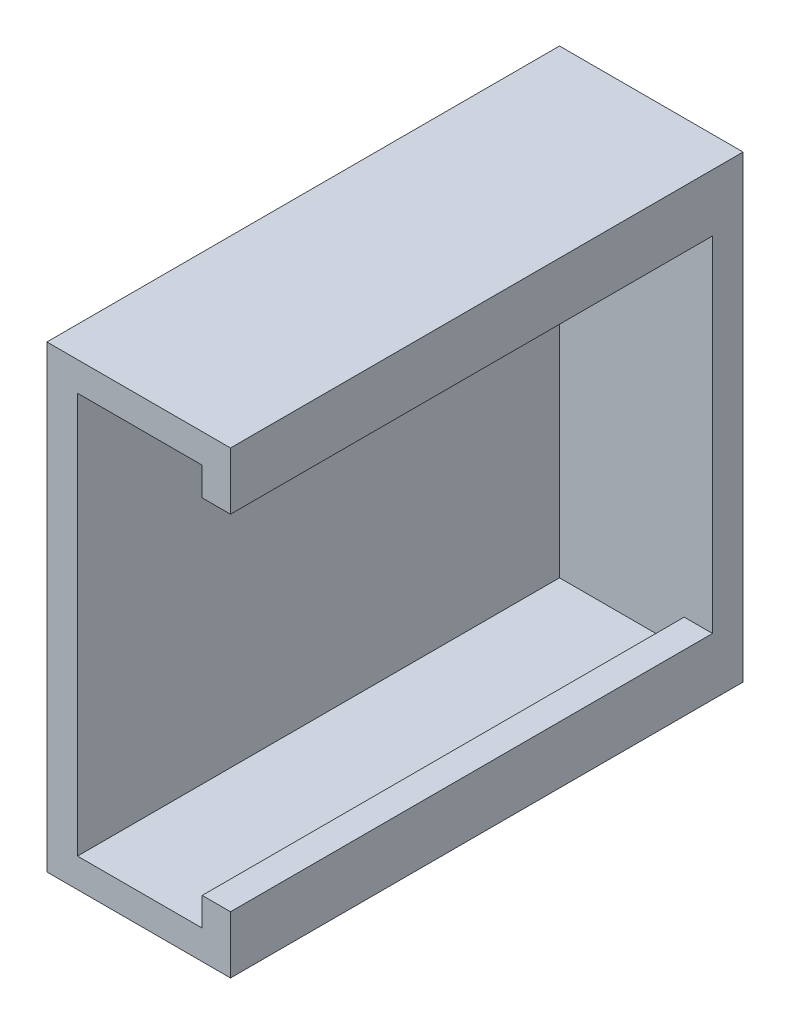
SolidWorks part; units mm, degrees
material "Alliage 1060"
ref_plane "Plan de dessus" through (0, 0, 0) normal (0, 0, 1) x (1, 0, 0)
ref_plane "Plan de droite" through (0, 0, 0) normal (0, 1, 0) x (1, 0, 0)
ref_plane "Plan de face" through (0, 0, 0) normal (1, 0, 0) x (0, 0, -1)
sketch "Esquisse1" plane through (0, 0, 0) normal (0, 0, 1) x (1, 0, 0)
  line L1 (0, 0) -> (24, 0)
  line L2 (0, 0) -> (0, 60)
  line L3 (0, 60) -> (24, 60)
  line L4 (24, 0) -> (24, 60)
  dimension "D1" = 24
  dimension "D2" = 60
extrude "Boss.-Extru.1" add sketch "Esquisse1" along normal blind 4
sketch "Esquisse2" plane through (0, 0, 4) normal (0, 0, 1) x (1, 0, 0)
  line L0 (24, 52.5) -> (20.3, 52.5)
  line L1 (24, 0) -> (24, 60) construction
  line L2 (20.3, 52.5) -> (20.3, 56.2)
  line L3 (20.3, 56.2) -> (4, 56.2)
  line L4 (4, 56.2) -> (4, 3.8)
  line L5 (4, 3.8) -> (20.3, 3.8)
  line L6 (20.3, 3.8) -> (20.3, 7.5)
  line L7 (20.3, 7.5) -> (24, 7.5)
  line L8 (24, 7.5) -> (24, 0)
  line L9 (24, 0) -> (0, 0)
  line L10 (0, 0) -> (0, 60)
  line L11 (0, 60) -> (24, 60)
  line L12 (24, 60) -> (24, 52.5)
  dimension "D1" = 7.5
  dimension "D2" = 3.7
  dimension "D3" = 3.7
  dimension "D4" = 3.7
  dimension "D5" = 7.5
  dimension "D6" = 3.7
  dimension "D7" = 4
extrude "Boss.-Extru.2" add sketch "Esquisse2" along normal blind 63
